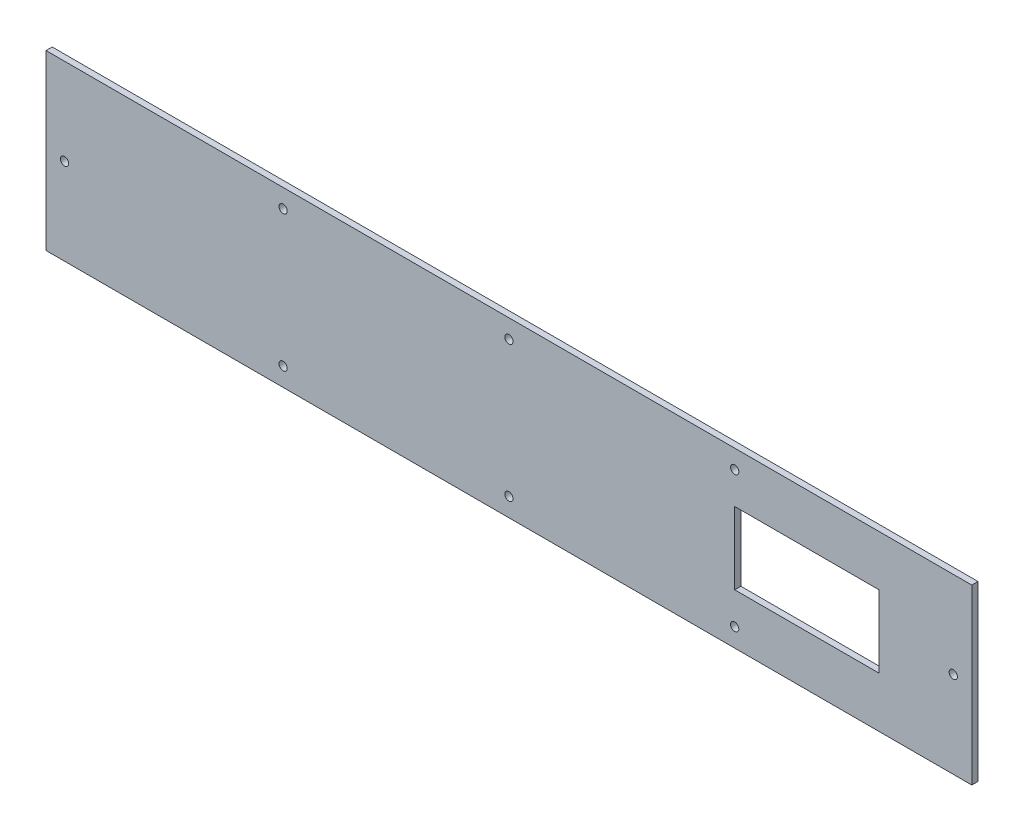
SolidWorks part; units mm, degrees
ref_plane "Piano frontale" through (0, 0, 0) normal (0, 0, 1) x (1, 0, 0)
ref_plane "Piano superiore" through (0, 0, 0) normal (0, 1, 0) x (1, 0, 0)
ref_plane "Piano destro" through (0, 0, 0) normal (1, 0, 0) x (0, 0, -1)
sketch "f" plane through (0, 0, 0) normal (0, 0, 1) x (1, 0, 0)
  line L0 (0, 0) -> (0, 84)
  line L1 (0, 84) -> (449, 84)
  line L2 (449, 84) -> (449, 0)
  line L3 (449, 0) -> (0, 0)
  line L4 (0, 42) -> (449, 42) construction
  line L5 (224.5, 42) -> (224.5, 123.488) construction
  line L6 (334, 59.5) -> (334, 24.5)
  line L7 (334, 24.5) -> (404, 24.5)
  line L8 (404, 24.5) -> (404, 59.5)
  line L9 (404, 59.5) -> (334, 59.5)
  line L10 (449, 84) -> (224.5, 0) construction
  line L11 (334, 42) -> (334, 84) construction
  line L12 (224.5, 0) -> (0, 84) construction
  line L13 (112.25, 42) -> (112.25, 84) construction
  circle A0 centre (9, 42) radius 2
  circle A1 centre (224.5, 75) radius 2
  circle A2 centre (224.5, 9) radius 2
  circle A3 centre (440, 42) radius 2
  circle A4 centre (334, 75) radius 2
  circle A5 centre (334, 9) radius 2
  circle A6 centre (115, 9) radius 2
  circle A7 centre (115, 75) radius 2
  dimension "D3" = 9
  dimension "D4" = 9
  dimension "D6" = 4
  dimension "D9" = 4
  dimension "D10" = 4
  dimension "D1" = 84
  dimension "D2" = 449
  dimension "D5" = 45
  dimension "D7" = 70
  dimension "D8" = 35
  dimension "D11" = 9
  dimension "D12" = 9
extrude "Estrusione-Estrusione1" add sketch "f" along normal blind 3
